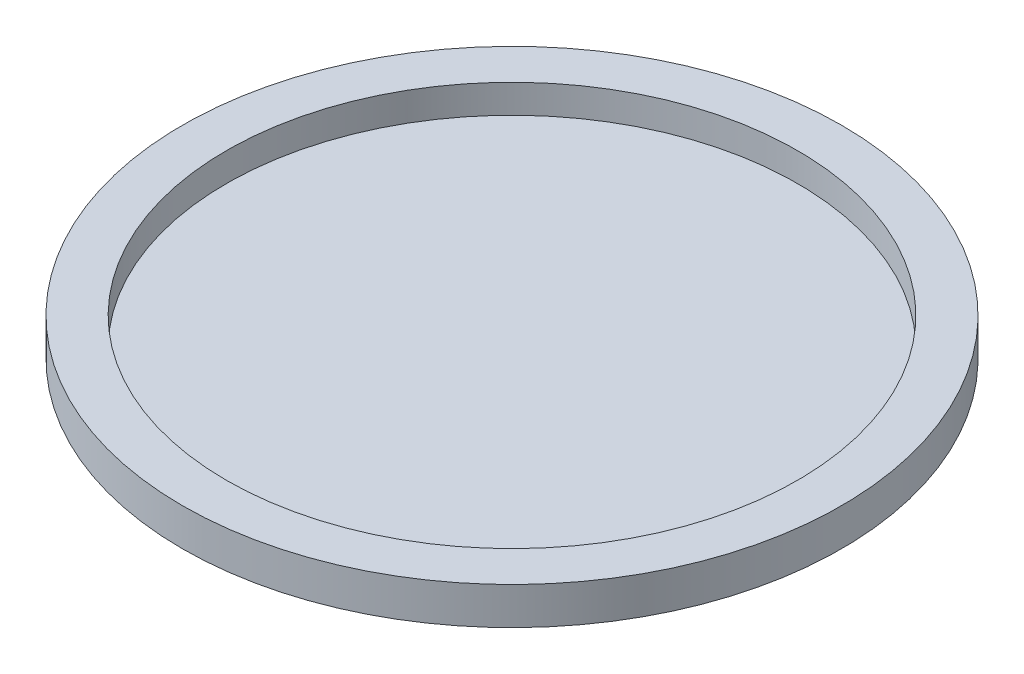
SolidWorks part; units mm, degrees
ref_plane "Спереди" through (0, 0, 0) normal (0, 0, 1) x (1, 0, 0)
ref_plane "Сверху" through (0, 0, 0) normal (0, 1, 0) x (1, 0, 0)
ref_plane "Справа" through (0, 0, 0) normal (1, 0, 0) x (0, 0, -1)
sketch "Эскиз1" plane through (0, 0, 0) normal (0, 1, 0) x (1, 0, 0)
  circle A0 centre (0, 0) radius 15
extrude "Бобышка-Вытянуть1" add sketch "Эскиз1" along normal blind 1.7
sketch "Эскиз2" plane through (0, 0, 0) normal (0, -1, 0) x (1, 0, 0)
  circle A0 centre (0, 0) radius 13.4036
extrude "Бобышка-Вытянуть2" add sketch "Эскиз2" along normal blind 1.2
fillet "Скругление1" radius 1 1 edges at (0, -1.2, -13.4036)
sketch "Эскиз4" plane through (0, -1.2, 0) normal (0, -1, 0) x (1, 0, 0)
  circle A0 centre (0, 0) radius 7.1533
extrude "Бобышка-Вытянуть3" add sketch "Эскиз4" along normal blind 2.1
sketch "Эскиз6" plane through (0, 1.7, 0) normal (0, 1, 0) x (1, 0, 0)
  circle A0 centre (0, 0) radius 12.9986
extrude "Вырез-Вытянуть4" cut sketch "Эскиз6" against normal blind 1.3
